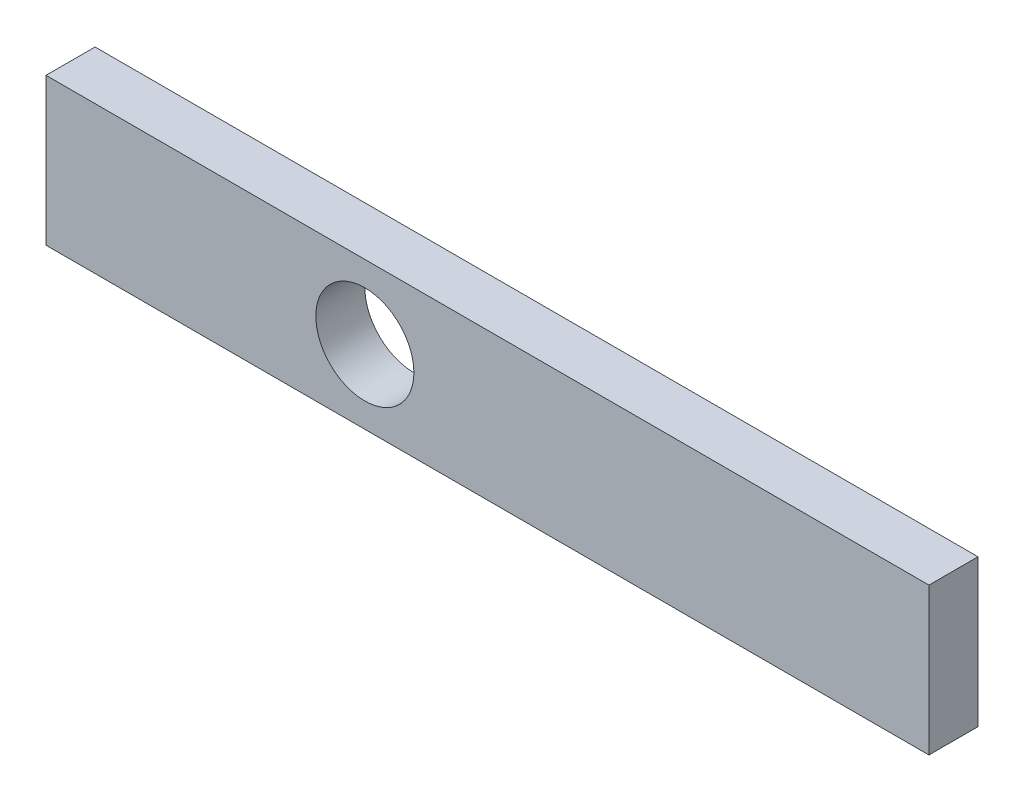
SolidWorks part; units mm, degrees
material "Acier allié"
ref_plane "Plan de face" through (0, 0, 0) normal (0, 0, 1) x (1, 0, 0)
ref_plane "Plan de dessus" through (0, 0, 0) normal (0, 1, 0) x (1, 0, 0)
ref_plane "Plan de droite" through (0, 0, 0) normal (1, 0, 0) x (0, 0, -1)
sketch "Esquisse1" plane through (0, 0, 0) normal (0, 0, 1) x (1, 0, 0)
  line L1 (90, 15) -> (-90, 15)
  line L2 (90, 15) -> (90, -15)
  line L3 (90, -15) -> (-90, -15)
  line L4 (-90, 15) -> (-90, -15)
  line L5 (90, 15) -> (-90, -15) construction
  line L6 (90, -15) -> (-90, 15) construction
  circle A0 centre (-25, 0) radius 10
  point P0 (0, 0)
  dimension "D1" = 20
  dimension "D2" = 30
  dimension "D3" = 180
  dimension "D4" = 25
extrude "Boss.-Extru.1" add sketch "Esquisse1" along normal blind 10
